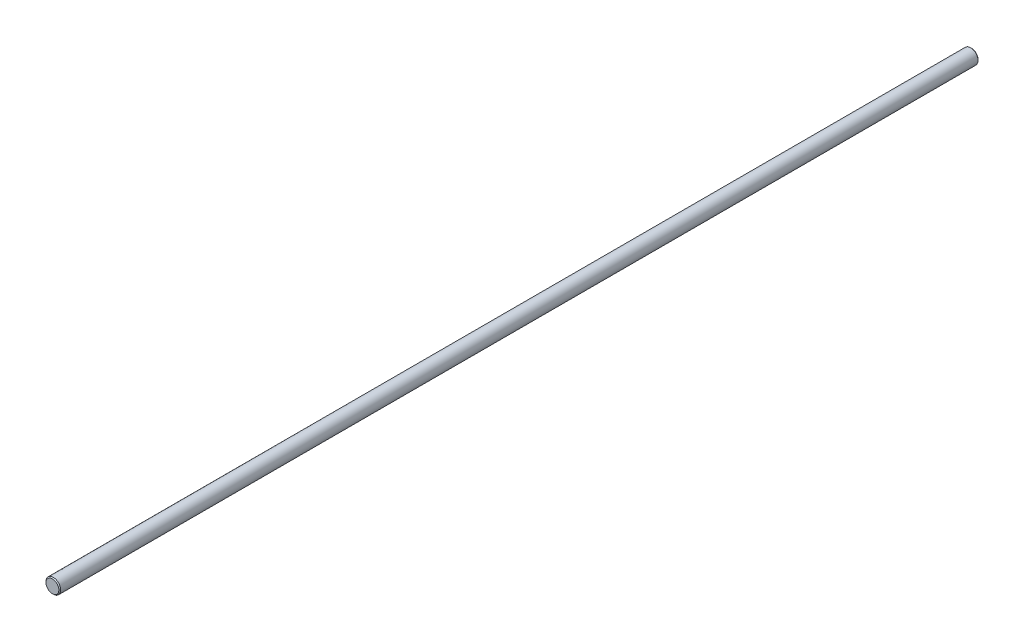
SolidWorks part; units mm, degrees
ref_plane "Front Plane" through (0, 0, 0) normal (0, 0, 1) x (1, 0, 0)
ref_plane "Top Plane" through (0, 0, 0) normal (0, 1, 0) x (1, 0, 0)
ref_plane "Right Plane" through (0, 0, 0) normal (1, 0, 0) x (0, 0, -1)
sketch "Sketch1" plane through (0, 0, 0) normal (0, 0, 1) x (1, 0, 0)
  circle A0 centre (0, 0) radius 8
  dimension "D1" = 16
extrude "Corpo" add sketch "Sketch1" against normal blind 1000
chamfer "Chanfros 1x45°" distance 1 angle 45 2 edges at (8, 0, -1000) (8, 0, 0)
